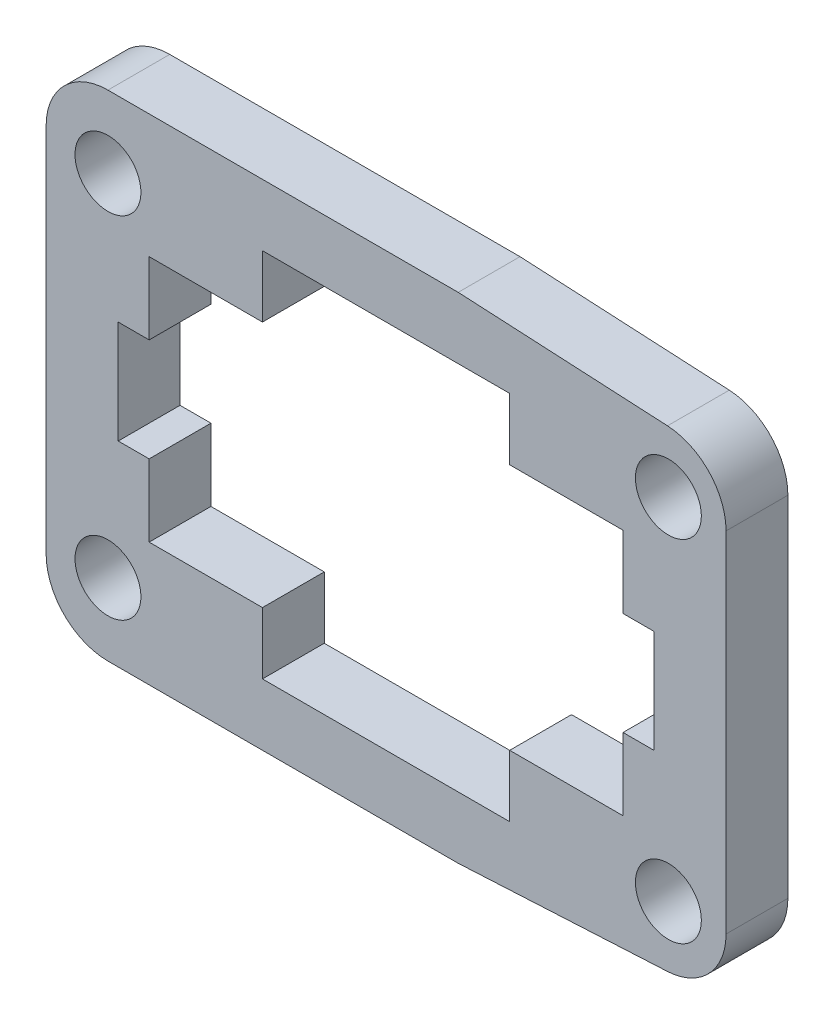
SolidWorks part; units mm, degrees
ref_plane "前视基准面" through (0, 0, 0) normal (0, 0, 1) x (1, 0, 0)
ref_plane "上视基准面" through (0, 0, 0) normal (0, 1, 0) x (1, 0, 0)
ref_plane "右视基准面" through (0, 0, 0) normal (1, 0, 0) x (0, 0, -1)
ref_plane "基准面4" through (0, 0, 3) normal (0, 0, 1) x (1, 0, 0)
sketch "草图1" plane through (0, 0, 3) normal (0, 0, 1) x (1, 0, 0)
  line L0 (13.8437, 23.9998) -> (-3.1571, 23.9998)
  line L1 (-6.1571, 20.9998) -> (-6.1571, 3)
  line L2 (-3.1571, 0) -> (13.8437, 0)
  line L3 (13.8437, 0) -> (24.0014, 0.533)
  line L4 (26.8442, 3.5289) -> (26.8442, 20.4719)
  line L5 (24.0011, 23.4678) -> (13.8437, 23.9998)
  line L6 (21.8432, 14.4995) -> (23.3435, 14.4995)
  line L7 (23.3435, 14.4995) -> (23.3435, 9.5)
  line L8 (23.3435, 9.5) -> (21.8432, 9.5)
  line L9 (21.8432, 9.5) -> (21.8432, 6)
  line L10 (21.8432, 6) -> (16.3434, 6)
  line L11 (16.3434, 6) -> (16.3434, 3)
  line L12 (16.3434, 3) -> (4.3434, 3)
  line L13 (4.3434, 3) -> (4.3434, 6)
  line L14 (4.3434, 6) -> (-1.1565, 6)
  line L15 (-1.1565, 6) -> (-1.1565, 9.5)
  line L16 (-1.1565, 9.5) -> (-2.6568, 9.5)
  line L17 (-2.6568, 9.5) -> (-2.6568, 14.4995)
  line L18 (-2.6568, 14.4995) -> (-1.1565, 14.4995)
  line L19 (-1.1565, 14.4995) -> (-1.1565, 17.9998)
  line L20 (-1.1565, 17.9998) -> (4.3434, 17.9998)
  line L21 (4.3434, 17.9998) -> (4.3434, 20.9998)
  line L22 (4.3434, 20.9998) -> (16.3434, 20.9998)
  line L23 (16.3434, 20.9998) -> (16.3434, 17.9998)
  line L24 (16.3434, 17.9998) -> (21.8432, 17.9998)
  line L25 (21.8432, 17.9998) -> (21.8432, 14.4995)
  arc A0 (-3.1571, 23.9998) -> (-6.1571, 20.9998) centre (-3.1571, 20.9998) ccw
  arc A1 (-6.1571, 3) -> (-3.1571, 0) centre (-3.1571, 3) ccw
  arc A2 (24.0014, 0.533) -> (26.8442, 3.5289) centre (23.8442, 3.5289) ccw
  arc A3 (26.8442, 20.4719) -> (24.0011, 23.4678) centre (23.8442, 20.4719) ccw
  circle A4 centre (24.044, 3.5011) radius 1.35
  circle A5 centre (-3.156, 3.5011) radius 1.35
  circle A6 centre (24.044, 20.4984) radius 1.35
  circle A7 centre (-3.156, 20.4984) radius 1.35
extrude "凸台-拉伸1" add sketch "草图1" against normal blind 3
sketch "草图2" plane through (0, 0, 3) normal (0, 0, 1) x (1, 0, 0)
  circle A0 centre (-3.156, 20.4984) radius 1.6
  circle A1 centre (24.044, 20.4984) radius 1.6
  circle A2 centre (24.044, 3.5011) radius 1.6
  circle A3 centre (-3.156, 3.5011) radius 1.6
  dimension "D1" = 3.2
extrude "切除-拉伸1" cut sketch "草图2" against normal through all
